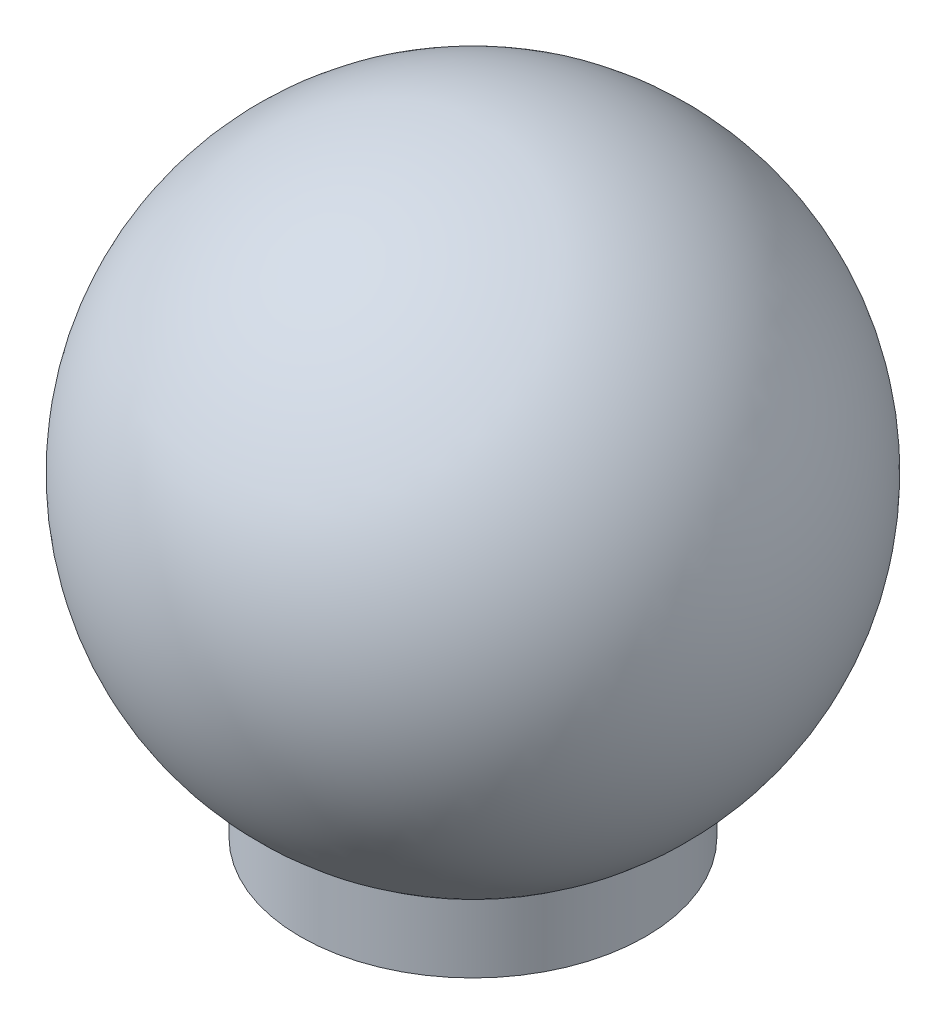
SolidWorks part; units mm, degrees
material "AISI 4340 Steel, normalized"
ref_plane "Front Plane" through (0, 0, 0) normal (0, 0, 1) x (1, 0, 0)
ref_plane "Top Plane" through (0, 0, 0) normal (0, 1, 0) x (1, 0, 0)
ref_plane "Right Plane" through (0, 0, 0) normal (1, 0, 0) x (0, 0, -1)
sketch "Sketch1" plane through (0, 0, 0) normal (0, 1, 0) x (1, 0, 0)
  circle A0 centre (0, 0) radius 25.4
  dimension "D1" = 50.8
extrude "Boss-Extrude1" add sketch "Sketch1" along normal blind 10
sketch "Sketch2" plane through (0, 0, 0) normal (0, 0, 1) x (1, 0, 0)
  line L0 (0, 145.4603) -> (0, 10)
  line L1 (25.4, 10) -> (-25.4, 10) construction
  line L2 (0, 10) -> (25.4, 10)
  line L3 (25.4, 0) -> (25.4, 10) construction
  circle A0 centre (0, 46.478) radius 44.45
  dimension "D1" = 88.9
revolve "Revolve1" add sketch "Sketch2" angle 360 about L0
ref_plane "Plane1" [suppressed] through (0, 58.42, 0) normal (0, 1, 0) x (1, 0, 0)
sketch "Sketch3" [suppressed] plane through (0, 58.42, 0) normal (0, 1, 0) x (1, 0, 0)
  line L1 (-57.15, 57.15) -> (57.15, 57.15)
  line L2 (-57.15, 57.15) -> (-57.15, -57.15)
  line L3 (-57.15, -57.15) -> (57.15, -57.15)
  line L4 (57.15, 57.15) -> (57.15, -57.15)
  circle A0 centre (0, 0) radius 44.45 construction
  point P5 (0, -57.15)
  point P7 (57.15, 0)
  point P10 (0, 44.45)
  point P11 (44.45, 0)
  dimension "D1" = 12.7
  dimension "D2" = 12.7
extrude "Boss-Extrude2" [suppressed] add sketch "Sketch3" along normal blind 50.8
fillet "Fillet1" [suppressed] radius 25.4
sketch "Sketch4" plane through (0, 0, 0) normal (0, -1, 0) x (1, 0, 0)
  point P0 (0, 0)
